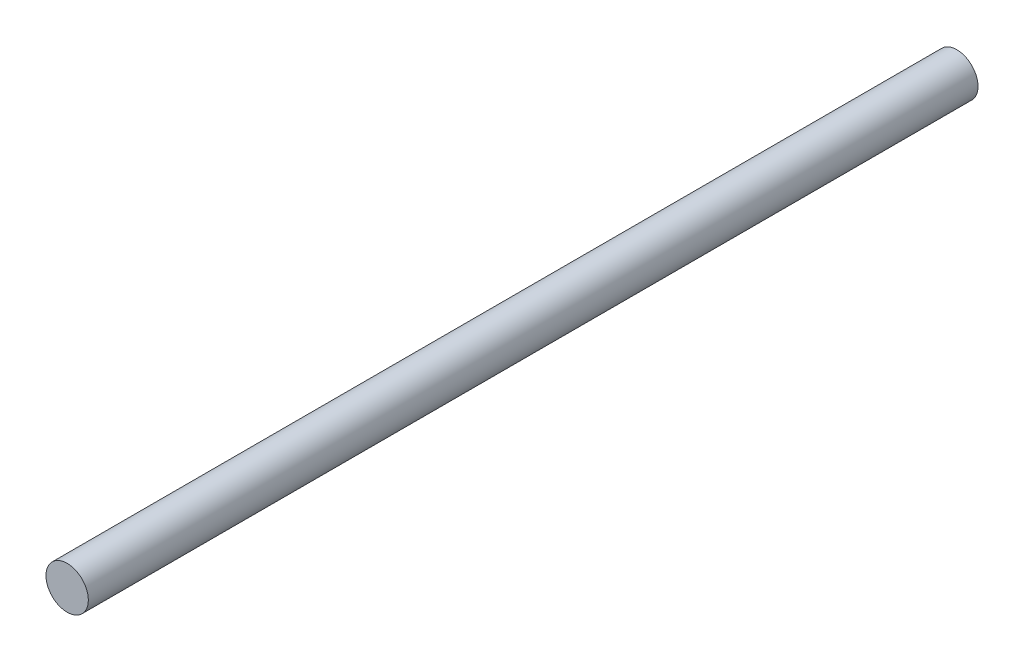
SolidWorks part; units mm, degrees
material "Hexcel AS4C (3000 Filaments)"
ref_plane "Front Plane" through (0, 0, 0) normal (0, 0, 1) x (1, 0, 0)
ref_plane "Top Plane" through (0, 0, 0) normal (0, 1, 0) x (1, 0, 0)
ref_plane "Right Plane" through (0, 0, 0) normal (1, 0, 0) x (0, 0, -1)
sketch "Sketch1" plane through (0, 0, 0) normal (0, 0, 1) x (1, 0, 0)
  circle A0 centre (0, 0) radius 2.5
  dimension "D1" = 5
extrude "Boss-Extrude1" add sketch "Sketch1" along normal blind 105
